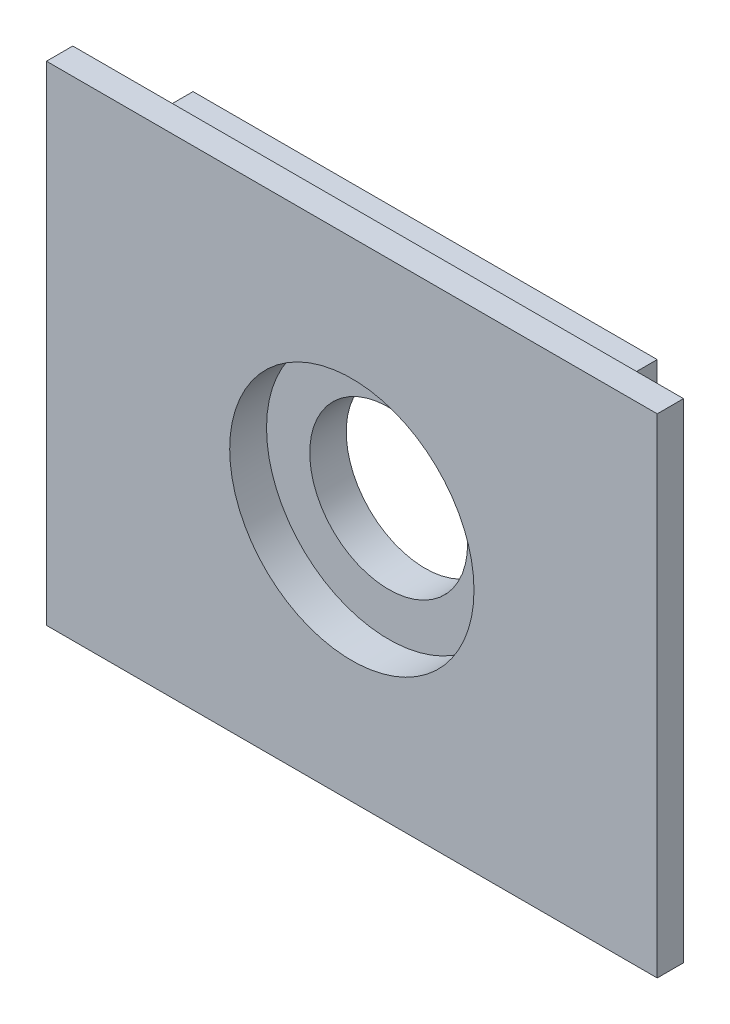
SolidWorks part; units mm, degrees
ref_plane "Front Plane" through (0, 0, 0) normal (0, 0, 1) x (1, 0, 0)
ref_plane "Top Plane" through (0, 0, 0) normal (0, 1, 0) x (1, 0, 0)
ref_plane "Right Plane" through (0, 0, 0) normal (1, 0, 0) x (0, 0, -1)
sketch "Sketch1" plane through (0, 0, 0) normal (0, 0, 1) x (1, 0, 0)
  line L1 (0, 0) -> (325, 0)
  line L2 (0, 0) -> (0, 260)
  line L3 (0, 260) -> (325, 260)
  line L4 (325, 0) -> (325, 260)
  dimension "D1" = 260
  dimension "D2" = 325
extrude "Boss-Extrude1" add sketch "Sketch1" against normal blind 39
sketch "Sketch2" plane through (0, 0, 0) normal (0, 0, 1) x (1, 0, 0)
  line L0 (325, 0) -> (325, 260) construction
  line L1 (325, 260) -> (0, 260) construction
  circle A0 centre (162.5, 130) radius 65
  point P5 (325, 130)
  point P8 (162.5, 260)
  dimension "D1" = 130
extrude "Cut-Extrude1" cut sketch "Sketch2" against normal blind 19.6
sketch "Sketch3" plane through (0, 0, 0) normal (0, 0, 1) x (1, 0, 0)
  circle A0 centre (162.5, 130) radius 42
  dimension "D1" = 84
extrude "Cut-Extrude2" cut sketch "Sketch3" against normal through all
ref_plane "Plane1" through (0, 0, -39) normal (0, 0, -1) x (-1, 0, 0)
sketch "Sketch4" plane through (0, 0, -39) normal (0, 0, -1) x (-1, 0, 0)
  line L1 (-325, 260) -> (0, 260)
  line L2 (-325, 260) -> (-325, 0)
  line L3 (-325, 0) -> (0, 0)
  line L4 (0, 260) -> (0, 0)
  line L5 (-286, 246) -> (-39, 246)
  line L6 (-286, 246) -> (-286, 14)
  line L7 (-286, 14) -> (-39, 14)
  line L8 (-39, 246) -> (-39, 14)
  point P10 (-162.5, 246)
  point P11 (-162.5, 260)
  point P12 (-39, 130)
  point P13 (0, 130)
  dimension "D1" = 14
  dimension "D2" = 39
extrude "Cut-Extrude3" cut sketch "Sketch4" against normal blind 25
